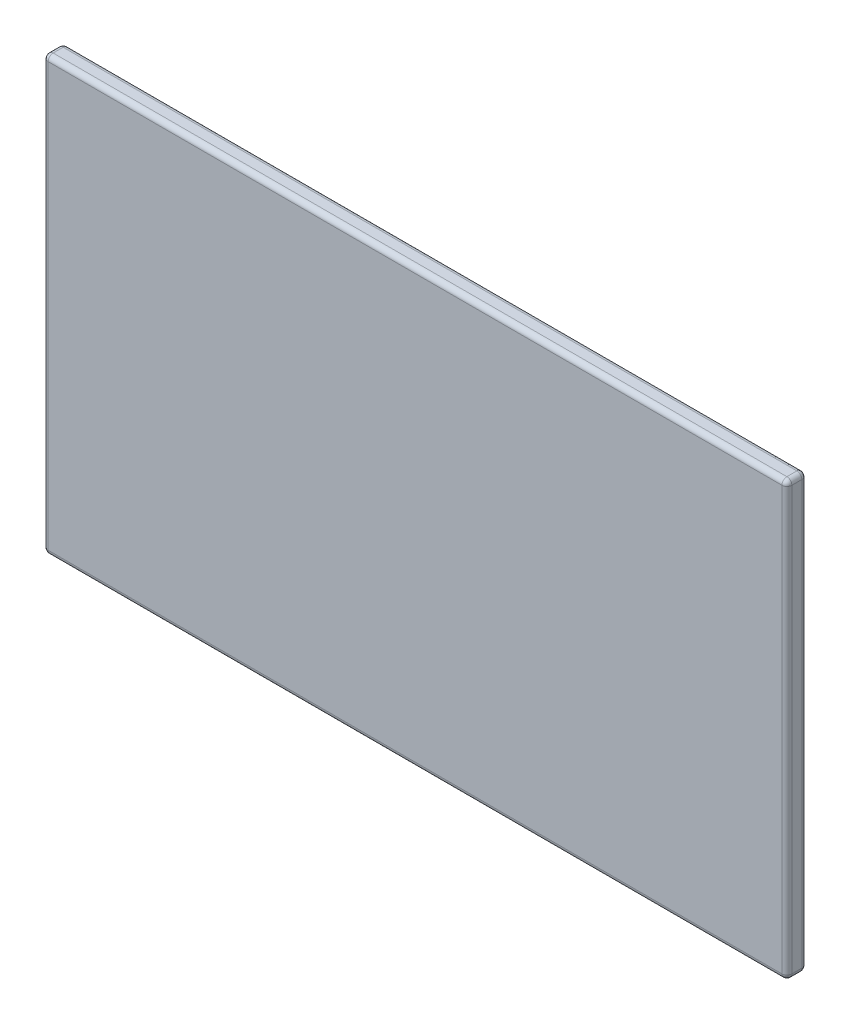
SolidWorks part; units mm, degrees
ref_plane "Front Plane" through (0, 0, 0) normal (0, 0, 1) x (1, 0, 0)
ref_plane "Top Plane" through (0, 0, 0) normal (0, 1, 0) x (1, 0, 0)
ref_plane "Right Plane" through (0, 0, 0) normal (1, 0, 0) x (0, 0, -1)
sketch "Sketch1" plane through (0, 0, 0) normal (0, 0, 1) x (1, 0, 0)
  line L1 (-37.35, -21.75) -> (37.35, -21.75)
  line L2 (-37.35, -21.75) -> (-37.35, 21.75)
  line L3 (-37.35, 21.75) -> (37.35, 21.75)
  line L4 (37.35, -21.75) -> (37.35, 21.75)
  line L5 (-37.35, -21.75) -> (37.35, 21.75) construction
  line L6 (-37.35, 21.75) -> (37.35, -21.75) construction
  point P0 (0, 0)
  dimension "D1" = 74.7
  dimension "D2" = 43.5
extrude "Boss-Extrude1" add sketch "Sketch1" along normal blind 2
fillet "Fillet1" radius 0.5 12 edges at (0, -21.75, 2) (0, -21.75, 0) (-37.35, 0, 2) (-37.35, -21.75, 1) (-37.35, 0, 0) (0, 21.75, 2) (-37.35, 21.75, 1) (0, 21.75, 0) (37.35, -21.75, 1) (37.35, 0, 2) (37.35, 21.75, 1) (37.35, 0, 0)
